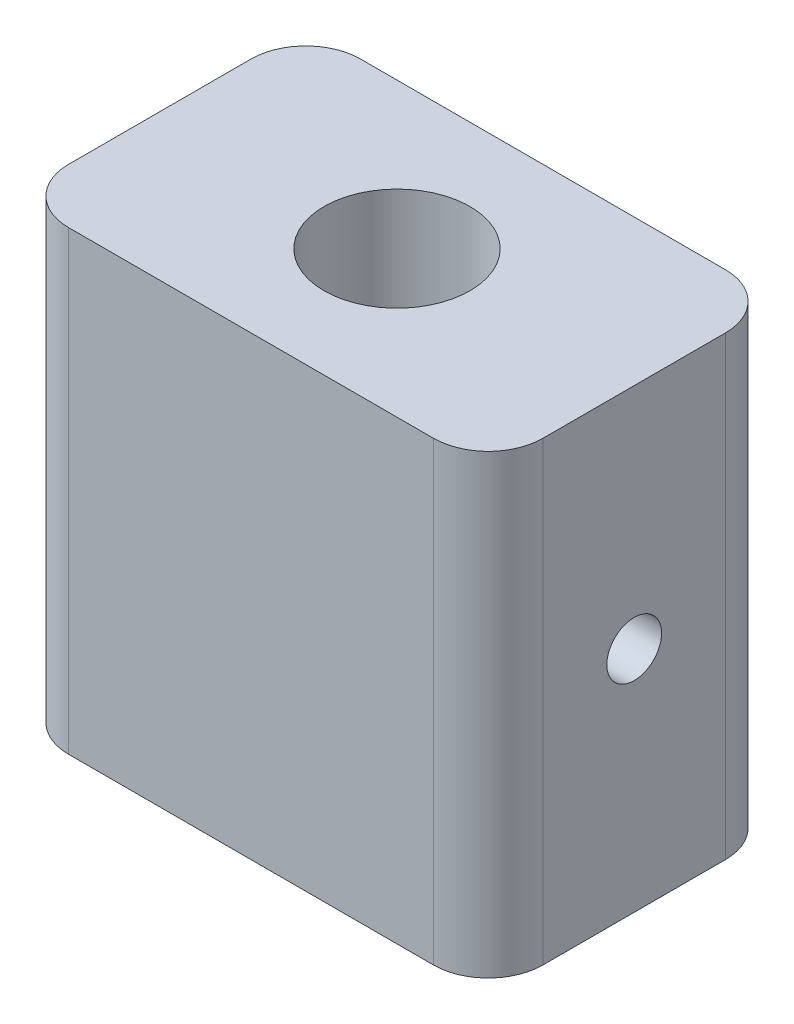
SolidWorks part; units mm, degrees
material "Brass"
ref_plane "Front Plane" through (0, 0, 0) normal (0, 0, 1) x (1, 0, 0)
ref_plane "Top Plane" through (0, 0, 0) normal (0, 1, 0) x (1, 0, 0)
ref_plane "Right Plane" through (0, 0, 0) normal (1, 0, 0) x (0, 0, -1)
sketch "Sketch1" plane through (0, 0, 0) normal (0, 1, 0) x (1, 0, 0)
  line L1 (10, -8) -> (-10, -8)
  line L2 (13, -5) -> (13, 5)
  line L3 (10, 8) -> (-10, 8)
  line L4 (-13, -5) -> (-13, 5)
  line L5 (13, -8) -> (-13, 8) construction
  line L6 (13, 8) -> (-13, -8) construction
  circle A0 centre (0, 0) radius 4
  arc A1 (-10, -8) -> (-13, -5) centre (-10, -5) cw
  arc A2 (10, -8) -> (13, -5) centre (10, -5) ccw
  arc A3 (13, 5) -> (10, 8) centre (10, 5) ccw
  arc A4 (-10, 8) -> (-13, 5) centre (-10, 5) ccw
  dimension "D1" = 8
  dimension "D4" = 3
  dimension "D2" = 26
  dimension "D3" = 16
extrude "Boss-Extrude1" add sketch "Sketch1" along normal blind 25
sketch "Sketch2" plane through (13, 0, 0) normal (1, 0, 0) x (0, 0, -1)
  line L0 (-5, 12.5) -> (5, 12.5) construction
  line L1 (-5, 25) -> (-5, 0) construction
  line L2 (5, 25) -> (5, 0) construction
  circle A0 centre (0, 12.5) radius 1.5
  dimension "D1" = 3
extrude "Cut-Extrude1" cut sketch "Sketch2" against normal blind 46 contours A0
